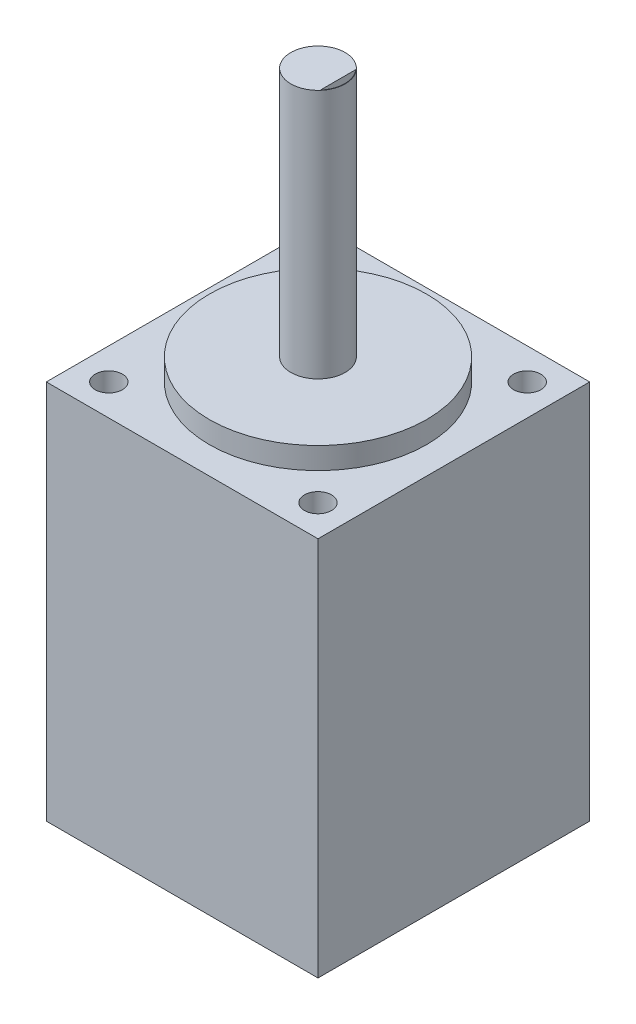
SolidWorks part; units mm, degrees
ref_plane "前视基准面" through (0, 0, 0) normal (0, 0, 1) x (1, 0, 0)
ref_plane "上视基准面" through (0, 0, 0) normal (0, 1, 0) x (1, 0, 0)
ref_plane "右视基准面" through (0, 0, 0) normal (1, 0, 0) x (0, 0, -1)
sketch "草图1" plane through (0, 0, 0) normal (0, 1, 0) x (1, 0, 0)
  line L0 (0, 0) -> (20, 0)
  line L1 (20, 0) -> (20, 20)
  line L2 (0, 0) -> (0, 20)
  line L3 (0, 20) -> (20, 20)
  circle A0 centre (17.7, 2.3) radius 1
  circle A1 centre (17.7, 17.7) radius 1
  circle A2 centre (2.3, 17.7) radius 1
  circle A3 centre (2.3, 2.3) radius 1
extrude "凸台-拉伸1" add sketch "草图1" along normal blind 28
sketch "草图2" plane through (0, 28, 0) normal (0, 1, 0) x (1, 0, 0)
  line L0 (20, 10) -> (0, 10)
  line L1 (20, 0) -> (20, 20) construction
  line L2 (0, 20) -> (0, 0) construction
  circle A0 centre (10, 10) radius 8
extrude "凸台-拉伸2" add sketch "草图2" along normal blind 1.6 contours L0 A0 | L0 A0
sketch "草图3" plane through (0, 29.6, 0) normal (0, 1, 0) x (1, 0, 0)
  circle A0 centre (10, 10) radius 2
extrude "凸台-拉伸3" add sketch "草图3" along normal blind 18.4
sketch "草图4" plane through (0, 48, 0) normal (0, 1, 0) x (1, 0, 0)
  line L0 (8, 10) -> (11.4813, 10)
  line L1 (11.4813, 10) -> (11.4813, 11.3042)
  line L2 (11.4813, 11.3042) -> (11.4813, 8.6958)
  circle A0 centre (10, 10) radius 2 construction
  circle A1 centre (10, 10) radius 2 construction
  circle A2 centre (10, 10) radius 1.9736
  circle M3 centre (10, 10) radius 2
extrude "切除-拉伸1" cut sketch "草图4" against normal blind 15 contours L1 L2 M3
